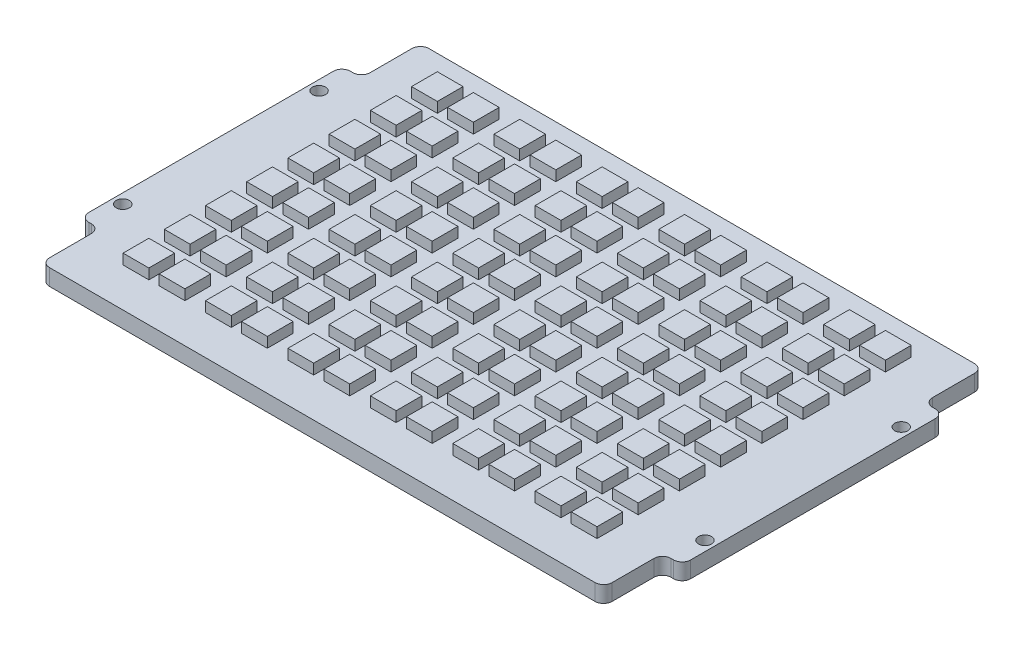
SolidWorks part; units mm, degrees
ref_plane "Front Plane" through (0, 0, 0) normal (0, 0, 1) x (1, 0, 0)
ref_plane "Top Plane" through (0, 0, 0) normal (0, 1, 0) x (1, 0, 0)
ref_plane "Right Plane" through (0, 0, 0) normal (1, 0, 0) x (0, 0, -1)
sketch "Sketch1" plane through (0, 0, 0) normal (0, 1, 0) x (1, 0, 0)
  line L1 (-54.61, -36.83) -> (54.61, -36.83)
  line L2 (-54.61, -36.83) -> (-54.61, 36.83)
  line L3 (-54.61, 36.83) -> (54.61, 36.83)
  line L4 (54.61, -36.83) -> (54.61, 36.83)
  line L5 (-54.61, -36.83) -> (54.61, 36.83) construction
  line L6 (-54.61, 36.83) -> (54.61, -36.83) construction
  point P0 (0, 0)
  dimension "D1" = 109.22
  dimension "D2" = 73.66
extrude "Boss-Extrude1" add sketch "Sketch1" against normal blind 3.175
ref_plane "Plane1" through (0, 0, -31.75) normal (0, 0, 1) x (1, 0, 0)
sketch "Sketch2" plane through (0, 0, -31.75) normal (0, 0, 1) x (1, 0, 0)
  line L3 (-43.75, 0) -> (-46.25, 0)
  line L4 (-43.75, 2) -> (-43.75, 0) construction
  line L5 (-46.25, 0) -> (-46.25, 2)
  line L6 (-54.61, 0) -> (54.61, 0) construction
  line L7 (-41.25, 0) -> (-43.75, 0)
  line L8 (-46.25, 2) -> (-41.25, 2)
  line L9 (-41.25, 2) -> (-41.25, 0)
  line L10 (-39.25, 2) -> (-34.25, 2)
  line L11 (-34.25, 2) -> (-34.25, 0)
  line L12 (-34.25, 0) -> (-36.75, 0)
  line L13 (-39.25, 0) -> (-39.25, 2)
  line L14 (-39.25, 0) -> (-36.75, 0)
  point P5 (-45, 0)
  dimension "D1" = 2.5
  dimension "D2" = 2
  dimension "D3" = 45
  dimension "D4" = 2
  dimension "D5" = 2
  dimension "D6" = 5
extrude "Boss-Extrude3" add sketch "Sketch2" along normal blind 5
pattern_linear "LPattern1" count 6 spacing 16 along (1, 0, 0) count 8 spacing 8 along (0, 0, 1) of "Boss-Extrude3"
sketch "Sketch3" plane through (0, 0, 0) normal (0, 1, 0) x (1, 0, 0)
  line L0 (-54.61, 36.83) -> (-54.61, -36.83) construction
  line L1 (-54.61, 25.4) -> (-58.42, 25.4)
  line L2 (-54.61, 25.4) -> (-54.61, -25.4)
  line L3 (-54.61, -25.4) -> (-58.42, -25.4)
  line L4 (-58.42, 25.4) -> (-58.42, -25.4)
  line L5 (0, 0) -> (0, 36.83) construction
  line L6 (54.61, 36.83) -> (-54.61, 36.83) construction
  line L7 (58.42, 25.4) -> (58.42, -25.4)
  line L8 (54.61, -25.4) -> (58.42, -25.4)
  line L9 (54.61, 25.4) -> (54.61, -25.4)
  line L10 (54.61, 25.4) -> (58.42, 25.4)
  circle A0 centre (-56.515, 19.05) radius 1.27
  circle A1 centre (-56.515, -19.05) radius 1.27
  circle A2 centre (56.515, -19.05) radius 1.27
  circle A3 centre (56.515, 19.05) radius 1.27
  point P6 (-58.42, 0)
  point P11 (-56.515, 25.4)
  dimension "D3" = 2.54
  dimension "D1" = 3.81
  dimension "D2" = 50.8
  dimension "D4" = 19.05
  dimension "D5" = 2
extrude "Boss-Extrude2" add sketch "Sketch3" against normal blind 3.175
fillet "Fillet1" radius 1.651 12 edges at (54.61, -1.5875, -36.83) (54.61, -1.5875, -25.4) (58.42, -1.5875, -25.4) (58.42, -1.5875, 25.4) (54.61, -1.5875, 25.4) (54.61, -1.5875, 36.83) (-54.61, -1.5875, 36.83) (-54.61, -1.5875, 25.4) (-58.42, -1.5875, 25.4) (-58.42, -1.5875, -25.4) (-54.61, -1.5875, -25.4) (-54.61, -1.5875, -36.83)
